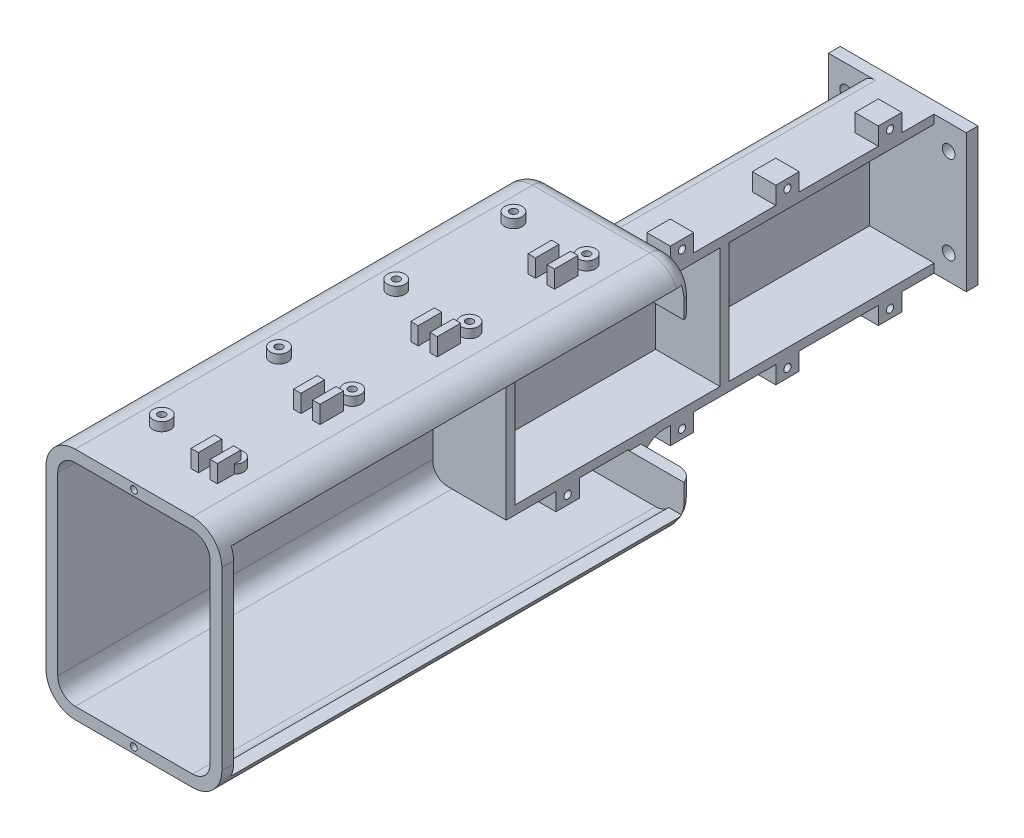
SolidWorks part; units mm, degrees
ref_plane "Front Plane" through (0, 0, 0) normal (0, 0, 1) x (1, 0, 0)
ref_plane "Top Plane" through (0, 0, 0) normal (0, 1, 0) x (1, 0, 0)
ref_plane "Right Plane" through (0, 0, 0) normal (1, 0, 0) x (0, 0, -1)
sketch "草圖1" plane through (0, 0, 0) normal (0, 0, 1) x (1, 0, 0)
  line L0 (-14, -23.5) -> (11, -23.5)
  line L1 (11, -23.5) -> (11, -20.5)
  line L2 (11, -20.5) -> (-11, -20.5)
  line L3 (-11, -20.5) -> (-11, 20.5)
  line L4 (-11, 20.5) -> (11, 20.5)
  line L5 (11, 20.5) -> (11, 23.5)
  line L6 (11, 23.5) -> (-14, 23.5)
  line L7 (-14, 23.5) -> (-14, -23.5)
extrude "填料-伸長1" add sketch "草圖1" along normal blind 150
fillet "圓角1" radius 5 2 edges at (-14, 23.5, 75) (-14, -23.5, 75)
sketch "草圖2" plane through (0, 0, 0) normal (0, 0, 1) x (1, 0, 0)
  line L0 (-25, -23.5) -> (22, -23.5)
  line L1 (22, -23.5) -> (22, 23.5)
  line L2 (22, 23.5) -> (-25, 23.5)
  line L3 (-25, 23.5) -> (-25, -23.5)
  circle A0 centre (-19, 15) radius 2.15
  circle A1 centre (-19, -15) radius 2.15
  circle A2 centre (16, 15) radius 2.15
  circle A3 centre (16, -15) radius 2.15
extrude "填料-伸長2" add sketch "草圖2" along normal blind 4
sketch "草圖3" plane through (0, 0, 0) normal (0, 0, 1) x (1, 0, 0)
  line L0 (-11.5, -21) -> (11, -21)
  line L1 (11, -21) -> (11, 21)
  line L2 (11, 21) -> (-11.5, 21)
  line L3 (-11.5, 21) -> (-11.5, -21)
extrude "填料-伸長3" add sketch "草圖3" along normal blind 3 from offset 74
sketch "草圖4" plane through (0, 0, 0) normal (0, 0, 1) x (1, 0, 0)
  line L0 (-11.5, -21) -> (11, -21)
  line L1 (11, -21) -> (11, 21)
  line L2 (11, 21) -> (-11.5, 21)
  line L3 (-11.5, 21) -> (-11.5, -21)
extrude "填料-伸長4" add sketch "草圖4" along normal blind 3 from offset 147
sketch "草圖5" plane through (0, 0, 0) normal (0, 0, 1) x (1, 0, 0)
  line L0 (30, -30) -> (30, 30)
  line L1 (20, 40) -> (-20, 40)
  line L2 (-30, 30) -> (-30, -30)
  line L3 (-20, -40) -> (20, -40)
  arc A0 (20, -40) -> (30, -30) centre (20, -30) ccw
  arc A1 (30, 30) -> (20, 40) centre (20, 30) ccw
  arc A2 (-20, 40) -> (-30, 30) centre (-20, 30) ccw
  arc A3 (-30, -30) -> (-20, -40) centre (-20, -30) ccw
extrude "填料-伸長5" add sketch "草圖5" along normal blind 4 from offset 104
sketch "草圖6" plane through (0, 0, 0) normal (0, 0, 1) x (1, 0, 0)
  line L0 (30, -30) -> (30, 30)
  line L1 (20, 40) -> (-20, 40)
  line L2 (-30, 30) -> (-30, -30)
  line L3 (-20, -40) -> (20, -40)
  line L4 (26, -30) -> (26, 30)
  line L5 (20, 36) -> (-20, 36)
  line L6 (-26, 30) -> (-26, -30)
  line L7 (-20, -36) -> (20, -36)
  arc A0 (20, -40) -> (30, -30) centre (20, -30) ccw
  arc A1 (30, 30) -> (20, 40) centre (20, 30) ccw
  arc A2 (-20, 40) -> (-30, 30) centre (-20, 30) ccw
  arc A3 (-30, -30) -> (-20, -40) centre (-20, -30) ccw
  arc A4 (20, -36) -> (26, -30) centre (20, -30) ccw
  arc A5 (26, 30) -> (20, 36) centre (20, 30) ccw
  arc A6 (-20, 36) -> (-26, 30) centre (-20, 30) ccw
  arc A7 (-26, -30) -> (-20, -36) centre (-20, -30) ccw
extrude "填料-伸長6" add sketch "草圖6" along normal blind 158 from offset 108
fillet "圓角2" radius 8 5 edges at (1, -23.5, 104) (-14, 0, 104) (-12.5355, 22.0355, 104) (1, 23.5, 104) (-12.5355, -22.0355, 104)
fillet "圓角3" radius 6 8 edges at (27.0711, -37.0711, 104) (30, 0, 104) (27.0711, 37.0711, 104) (0, 40, 104) (-27.0711, 37.0711, 104) (-30, 0, 104) (-27.0711, -37.0711, 104) (0, -40, 104)
sketch "草圖7" plane through (0, 0, 0) normal (0, 0, 1) x (1, 0, 0)
  line L0 (-11, -20.5) -> (35, -20.5)
  line L1 (35, -20.5) -> (35, 20.5)
  line L2 (35, 20.5) -> (-11, 20.5)
  line L3 (-11, 20.5) -> (-11, -20.5)
extrude "除料-伸長1" cut sketch "草圖7" along normal blind 70 from offset 77
sketch "草圖8" plane through (0, 0, 0) normal (0, 0, 1) x (1, 0, 0)
  line L0 (11, -24) -> (35, -24)
  line L1 (35, -24) -> (35, 24)
  line L2 (35, 24) -> (11, 24)
  line L3 (11, 24) -> (11, -24)
extrude "除料-伸長2" cut sketch "草圖8" along normal blind 5.5 from offset 103
sketch "草圖9" plane through (0, 0, 0) normal (0, 0, 1) x (1, 0, 0)
  line L0 (24, -34) -> (35, -34)
  line L1 (35, -34) -> (35, 34)
  line L2 (35, 34) -> (24, 34)
  line L3 (24, 34) -> (24, -34)
extrude "除料-伸長3" cut sketch "草圖9" along normal blind 154 from offset 108
sketch "草圖10" plane through (0, 0, 0) normal (0, 0, 1) x (1, 0, 0)
  circle A0 centre (0, 38) radius 1.15
  circle A1 centre (0, -38) radius 1.15
extrude "除料-伸長4" cut sketch "草圖10" along normal blind 8 from offset 258
sketch "草圖11" plane through (0, 0, 0) normal (0, 1, 0) x (1, 0, 0)
  circle A0 centre (-12.5, -124) radius 3
  circle A1 centre (-12.5, -124) radius 1.25
  circle A2 centre (-12.5, -164) radius 3
  circle A3 centre (-12.5, -164) radius 1.25
  circle A4 centre (-12.5, -204) radius 3
  circle A5 centre (-12.5, -204) radius 1.25
  circle A6 centre (-12.5, -244) radius 3
  circle A7 centre (-12.5, -244) radius 1.25
  circle A8 centre (12.5, -124) radius 3
  circle A9 centre (12.5, -124) radius 1.25
  circle A10 centre (12.5, -164) radius 3
  circle A11 centre (12.5, -164) radius 1.25
  circle A12 centre (12.5, -204) radius 3
  circle A13 centre (12.5, -204) radius 1.25
  circle A14 centre (12.5, -244) radius 3
  circle A15 centre (12.5, -244) radius 1.25
extrude "填料-伸長7" add sketch "草圖11" along normal blind 3 from offset 40
sketch "草圖12" plane through (0, 0, 0) normal (0, 1, 0) x (1, 0, 0)
  circle A0 centre (-12.5, -124) radius 3
  circle A1 centre (-12.5, -124) radius 1.25
  circle A2 centre (-12.5, -164) radius 3
  circle A3 centre (-12.5, -164) radius 1.25
  circle A4 centre (-12.5, -204) radius 3
  circle A5 centre (-12.5, -204) radius 1.25
  circle A6 centre (-12.5, -244) radius 3
  circle A7 centre (-12.5, -244) radius 1.25
  circle A8 centre (12.5, -124) radius 3
  circle A9 centre (12.5, -124) radius 1.25
  circle A10 centre (12.5, -164) radius 3
  circle A11 centre (12.5, -164) radius 1.25
  circle A12 centre (12.5, -204) radius 3
  circle A13 centre (12.5, -204) radius 1.25
  circle A14 centre (12.5, -244) radius 3
  circle A15 centre (12.5, -244) radius 1.25
extrude "填料-伸長8" add sketch "草圖12" against normal blind 3 from offset 40
sketch "草圖13" plane through (0, 0, 0) normal (1, 0, 0) x (0, 0, -1)
  circle A0 centre (-124, -15) radius 3
  circle A1 centre (-124, -15) radius 1.25
  circle A2 centre (-164, -15) radius 3
  circle A3 centre (-164, -15) radius 1.25
  circle A4 centre (-204, -15) radius 3
  circle A5 centre (-204, -15) radius 1.25
  circle A6 centre (-244, -15) radius 3
  circle A7 centre (-244, -15) radius 1.25
  circle A8 centre (-124, 15) radius 3
  circle A9 centre (-124, 15) radius 1.25
  circle A10 centre (-164, 15) radius 3
  circle A11 centre (-164, 15) radius 1.25
  circle A12 centre (-204, 15) radius 3
  circle A13 centre (-204, 15) radius 1.25
  circle A14 centre (-244, 15) radius 3
  circle A15 centre (-244, 15) radius 1.25
extrude "填料-伸長9" add sketch "草圖13" against normal blind 3 from offset 30
sketch "草圖14" plane through (0, 0, 0) normal (1, 0, 0) x (0, 0, -1)
  line L0 (-23, 23) -> (-15, 23)
  line L1 (-15, 23) -> (-15, 29.5)
  line L2 (-15, 29.5) -> (-23, 29.5)
  line L3 (-23, 29.5) -> (-23, 23)
  line L4 (-23, -29.5) -> (-15, -29.5)
  line L5 (-15, -29.5) -> (-15, -23)
  line L6 (-15, -23) -> (-23, -23)
  line L7 (-23, -23) -> (-23, -29.5)
  line L8 (-58, 23) -> (-50, 23)
  line L9 (-50, 23) -> (-50, 29.5)
  line L10 (-50, 29.5) -> (-58, 29.5)
  line L11 (-58, 29.5) -> (-58, 23)
  line L12 (-58, -29.5) -> (-50, -29.5)
  line L13 (-50, -29.5) -> (-50, -23)
  line L14 (-50, -23) -> (-58, -23)
  line L15 (-58, -23) -> (-58, -29.5)
  line L16 (-94, 23) -> (-86, 23)
  line L17 (-86, 23) -> (-86, 29.5)
  line L18 (-86, 29.5) -> (-94, 29.5)
  line L19 (-94, 29.5) -> (-94, 23)
  line L20 (-94, -29.5) -> (-86, -29.5)
  line L21 (-86, -29.5) -> (-86, -23)
  line L22 (-86, -23) -> (-94, -23)
  line L23 (-94, -23) -> (-94, -29.5)
  line L24 (-133, 23) -> (-125, 23)
  line L25 (-125, 23) -> (-125, 29.5)
  line L26 (-125, 29.5) -> (-133, 29.5)
  line L27 (-133, 29.5) -> (-133, 23)
  line L28 (-133, -29.5) -> (-125, -29.5)
  line L29 (-125, -29.5) -> (-125, -23)
  line L30 (-125, -23) -> (-133, -23)
  line L31 (-133, -23) -> (-133, -29.5)
  circle A0 centre (-19, 26.5) radius 1.25
  circle A1 centre (-19, -26.5) radius 1.25
  circle A2 centre (-54, 26.5) radius 1.25
  circle A3 centre (-54, -26.5) radius 1.25
  circle A4 centre (-90, 26.5) radius 1.25
  circle A5 centre (-90, -26.5) radius 1.25
  circle A6 centre (-129, 26.5) radius 1.25
  circle A7 centre (-129, -26.5) radius 1.25
extrude "填料-伸長10" add sketch "草圖14" along normal blind 8 from offset 3
sketch "草圖15" plane through (0, 0, 0) normal (0, 1, 0) x (1, 0, 0)
  line L0 (5.5, -129) -> (8, -129)
  line L1 (8, -129) -> (8, -137)
  line L2 (8, -137) -> (5.5, -137)
  line L3 (5.5, -137) -> (5.5, -129)
  line L4 (12, -129) -> (14.5, -129)
  line L5 (14.5, -129) -> (14.5, -137)
  line L6 (14.5, -137) -> (12, -137)
  line L7 (12, -137) -> (12, -129)
  line L8 (5.5, -169) -> (8, -169)
  line L9 (8, -169) -> (8, -177)
  line L10 (8, -177) -> (5.5, -177)
  line L11 (5.5, -177) -> (5.5, -169)
  line L12 (12, -169) -> (14.5, -169)
  line L13 (14.5, -169) -> (14.5, -177)
  line L14 (14.5, -177) -> (12, -177)
  line L15 (12, -177) -> (12, -169)
  line L16 (5.5, -209) -> (8, -209)
  line L17 (8, -209) -> (8, -217)
  line L18 (8, -217) -> (5.5, -217)
  line L19 (5.5, -217) -> (5.5, -209)
  line L20 (12, -209) -> (14.5, -209)
  line L21 (14.5, -209) -> (14.5, -217)
  line L22 (14.5, -217) -> (12, -217)
  line L23 (12, -217) -> (12, -209)
  line L24 (5.5, -244) -> (8, -244)
  line L25 (8, -244) -> (8, -252)
  line L26 (8, -252) -> (5.5, -252)
  line L27 (5.5, -252) -> (5.5, -244)
  line L28 (12, -244) -> (14.5, -244)
  line L29 (14.5, -244) -> (14.5, -252)
  line L30 (14.5, -252) -> (12, -252)
  line L31 (12, -252) -> (12, -244)
extrude "填料-伸長11" add sketch "草圖15" along normal blind 6 from offset 40
sketch "草圖16" plane through (0, 0, 0) normal (0, 1, 0) x (1, 0, 0)
  line L0 (5.5, -129) -> (8, -129)
  line L1 (8, -129) -> (8, -137)
  line L2 (8, -137) -> (5.5, -137)
  line L3 (5.5, -137) -> (5.5, -129)
  line L4 (12, -129) -> (14.5, -129)
  line L5 (14.5, -129) -> (14.5, -137)
  line L6 (14.5, -137) -> (12, -137)
  line L7 (12, -137) -> (12, -129)
  line L8 (5.5, -169) -> (8, -169)
  line L9 (8, -169) -> (8, -177)
  line L10 (8, -177) -> (5.5, -177)
  line L11 (5.5, -177) -> (5.5, -169)
  line L12 (12, -169) -> (14.5, -169)
  line L13 (14.5, -169) -> (14.5, -177)
  line L14 (14.5, -177) -> (12, -177)
  line L15 (12, -177) -> (12, -169)
  line L16 (5.5, -209) -> (8, -209)
  line L17 (8, -209) -> (8, -217)
  line L18 (8, -217) -> (5.5, -217)
  line L19 (5.5, -217) -> (5.5, -209)
  line L20 (12, -209) -> (14.5, -209)
  line L21 (14.5, -209) -> (14.5, -217)
  line L22 (14.5, -217) -> (12, -217)
  line L23 (12, -217) -> (12, -209)
  line L24 (5.5, -244) -> (8, -244)
  line L25 (8, -244) -> (8, -252)
  line L26 (8, -252) -> (5.5, -252)
  line L27 (5.5, -252) -> (5.5, -244)
  line L28 (12, -244) -> (14.5, -244)
  line L29 (14.5, -244) -> (14.5, -252)
  line L30 (14.5, -252) -> (12, -252)
  line L31 (12, -252) -> (12, -244)
extrude "填料-伸長12" add sketch "草圖16" against normal blind 6 from offset 40
